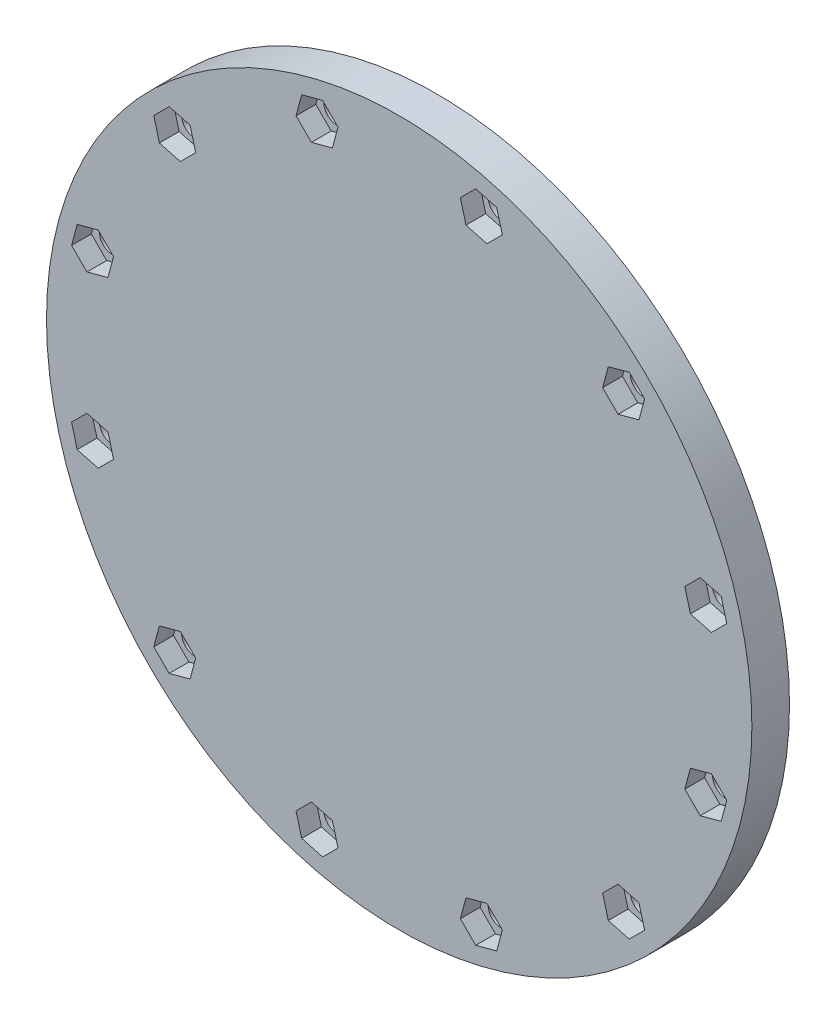
SolidWorks part; units mm, degrees
ref_plane "Front" through (0, 0, 0) normal (0, 0, 1) x (1, 0, 0)
ref_plane "Top" through (0, 0, 0) normal (0, 1, 0) x (1, 0, 0)
ref_plane "Right" through (0, 0, 0) normal (1, 0, 0) x (0, 0, -1)
sketch "Sketch1" plane through (0, 0, 0) normal (0, 0, 1) x (1, 0, 0)
  circle A0 centre (0, 0) radius 75
  dimension "D1" = 150
extrude "Boss-Extrude1" add sketch "Sketch1" along normal blind 8
hole_wizard "M5 Clearance Hole1" positions "Sketch3" profile "Sketch5" hole size "M5" standard "ANSI Metric" end condition up to next
sketch "Sketch3" plane through (0, 0, 0) normal (0, 0, -1) x (-1, 0, 0)
  line L14 (0, 0) -> (0, -75) construction
  line L15 (17.4703, -65.2) -> (-17.4703, 65.2) construction
  line L17 (65.2, 17.4703) -> (-65.2, -17.4703) construction
  line L19 (47.7297, 47.7297) -> (-47.7297, -47.7297) construction
  line L21 (0, 0) -> (17.4703, -65.2) construction
  line L23 (-17.4703, -65.2) -> (17.4703, 65.2) construction
  line L24 (-65.2, 17.4703) -> (65.2, -17.4703) construction
  line L26 (-47.7297, 47.7297) -> (47.7297, -47.7297) construction
  circle A1 centre (0, 0) radius 75 construction
  circle A3 centre (0, 0) radius 67.5 construction
  point P5 (-47.7297, 47.7297)
  point P11 (65.2, -17.4703)
  point P13 (47.7297, -47.7297)
  point P21 (-65.2, 17.4703)
  point P62 (-17.4703, 65.2)
  point P64 (-65.2, -17.4703)
  point P66 (-47.7297, -47.7297)
  point P68 (17.4703, -65.2)
  point P70 (17.4703, -65.2)
  point P72 (65.2, 17.4703)
  point P74 (47.7297, 47.7297)
  point P450 (17.4703, 65.2)
  point P453 (-17.4703, -65.2)
  dimension "D1" = 30
  dimension "D2" = 135
  dimension "D3" = 30
  dimension "D4" = 15
  dimension "D5" = 30
  dimension "D6" = 30
  dimension "D7" = 30
sketch "Sketch5" plane through (17.4703, -65.2, 0) normal (1, 0, 0) x (0, 1, 0)
  line L0 (0, 0) -> (0, 8)
  line L1 (0, 8) -> (2.75, 8)
  line L2 (2.75, 8) -> (2.75, 0)
  line L5 (2.75, 0) -> (0, 0)
  line L11 (0, -6.35) -> (0, 107.95) construction
  dimension "Thru Hole Dia." = 5.5
  dimension "Thru Hole Depth" = 8
sketch "Sketch6" plane through (0, 0, 8) normal (0, 0, -1) x (-1, 0, 0)
  line L0 (0, 0) -> (-47.7297, 47.7297) construction
  line L25 (-43.2683, 46.5343) -> (-44.4637, 50.9957)
  line L26 (-44.4637, 50.9957) -> (-48.9251, 52.1911)
  line L27 (-48.9251, 52.1911) -> (-52.1911, 48.9251)
  line L28 (-52.1911, 48.9251) -> (-50.9957, 44.4637)
  line L29 (-50.9957, 44.4637) -> (-46.5343, 43.2683)
  line L30 (-46.5343, 43.2683) -> (-43.2683, 46.5343)
  line L79 (-13.0089, 66.3954) -> (-16.2749, 69.6614)
  line L80 (-14.2043, 61.934) -> (-13.0089, 66.3954)
  line L81 (-18.6657, 60.7386) -> (-14.2043, 61.934)
  line L82 (-21.9317, 64.0046) -> (-18.6657, 60.7386)
  line L83 (-20.7363, 68.466) -> (-21.9317, 64.0046)
  line L84 (-16.2749, 69.6614) -> (-20.7363, 68.466)
  line L85 (21.9317, 64.0046) -> (20.7363, 68.466)
  line L86 (18.6657, 60.7386) -> (21.9317, 64.0046)
  line L87 (14.2043, 61.934) -> (18.6657, 60.7386)
  line L88 (13.0089, 66.3954) -> (14.2043, 61.934)
  line L89 (16.2749, 69.6614) -> (13.0089, 66.3954)
  line L90 (20.7363, 68.466) -> (16.2749, 69.6614)
  line L91 (50.9957, 44.4637) -> (52.1911, 48.9251)
  line L92 (46.5343, 43.2683) -> (50.9957, 44.4637)
  line L93 (43.2683, 46.5343) -> (46.5343, 43.2683)
  line L94 (44.4637, 50.9957) -> (43.2683, 46.5343)
  line L95 (48.9251, 52.1911) -> (44.4637, 50.9957)
  line L96 (52.1911, 48.9251) -> (48.9251, 52.1911)
  line L97 (66.3954, 13.0089) -> (69.6614, 16.2749)
  line L98 (61.934, 14.2043) -> (66.3954, 13.0089)
  line L99 (60.7386, 18.6657) -> (61.934, 14.2043)
  line L100 (64.0046, 21.9317) -> (60.7386, 18.6657)
  line L101 (68.466, 20.7363) -> (64.0046, 21.9317)
  line L102 (69.6614, 16.2749) -> (68.466, 20.7363)
  line L103 (64.0046, -21.9317) -> (68.466, -20.7363)
  line L104 (60.7386, -18.6657) -> (64.0046, -21.9317)
  line L105 (61.934, -14.2043) -> (60.7386, -18.6657)
  line L106 (66.3954, -13.0089) -> (61.934, -14.2043)
  line L107 (69.6614, -16.2749) -> (66.3954, -13.0089)
  line L108 (68.466, -20.7363) -> (69.6614, -16.2749)
  line L109 (44.4637, -50.9957) -> (48.9251, -52.1911)
  line L110 (43.2683, -46.5343) -> (44.4637, -50.9957)
  line L111 (46.5343, -43.2683) -> (43.2683, -46.5343)
  line L112 (50.9957, -44.4637) -> (46.5343, -43.2683)
  line L113 (52.1911, -48.9251) -> (50.9957, -44.4637)
  line L114 (48.9251, -52.1911) -> (52.1911, -48.9251)
  line L115 (13.0089, -66.3954) -> (16.2749, -69.6614)
  line L116 (14.2043, -61.934) -> (13.0089, -66.3954)
  line L117 (18.6657, -60.7386) -> (14.2043, -61.934)
  line L118 (21.9317, -64.0046) -> (18.6657, -60.7386)
  line L119 (20.7363, -68.466) -> (21.9317, -64.0046)
  line L120 (16.2749, -69.6614) -> (20.7363, -68.466)
  line L121 (-21.9317, -64.0046) -> (-20.7363, -68.466)
  line L122 (-18.6657, -60.7386) -> (-21.9317, -64.0046)
  line L123 (-14.2043, -61.934) -> (-18.6657, -60.7386)
  line L124 (-13.0089, -66.3954) -> (-14.2043, -61.934)
  line L125 (-16.2749, -69.6614) -> (-13.0089, -66.3954)
  line L126 (-20.7363, -68.466) -> (-16.2749, -69.6614)
  line L127 (-50.9957, -44.4637) -> (-52.1911, -48.9251)
  line L128 (-46.5343, -43.2683) -> (-50.9957, -44.4637)
  line L129 (-43.2683, -46.5343) -> (-46.5343, -43.2683)
  line L130 (-44.4637, -50.9957) -> (-43.2683, -46.5343)
  line L131 (-48.9251, -52.1911) -> (-44.4637, -50.9957)
  line L132 (-52.1911, -48.9251) -> (-48.9251, -52.1911)
  line L133 (-66.3954, -13.0089) -> (-69.6614, -16.2749)
  line L134 (-61.934, -14.2043) -> (-66.3954, -13.0089)
  line L135 (-60.7386, -18.6657) -> (-61.934, -14.2043)
  line L136 (-64.0046, -21.9317) -> (-60.7386, -18.6657)
  line L137 (-68.466, -20.7363) -> (-64.0046, -21.9317)
  line L138 (-69.6614, -16.2749) -> (-68.466, -20.7363)
  line L139 (-64.0046, 21.9317) -> (-68.466, 20.7363)
  line L140 (-60.7386, 18.6657) -> (-64.0046, 21.9317)
  line L141 (-61.934, 14.2043) -> (-60.7386, 18.6657)
  line L142 (-66.3954, 13.0089) -> (-61.934, 14.2043)
  line L143 (-69.6614, 16.2749) -> (-66.3954, 13.0089)
  line L144 (-68.466, 20.7363) -> (-69.6614, 16.2749)
  circle A6 centre (-47.7297, 47.7297) radius 4 construction
  circle A13 centre (-47.7297, 47.7297) radius 2.75 construction
  point P80 (0, 0)
  point P111 (-44.9013, 44.9013)
  dimension "D1" = 12
  dimension "D8" = 8
extrude "Cut-Extrude2" cut sketch "Sketch6" along normal blind 4.2
hole_wizard "Ø5.0mm Dowel Hole1" positions "Sketch8" profile "Sketch10" hole size "Ø5.0" standard "ANSI Metric"
sketch "Sketch8" plane through (0, 0, 0) normal (0, 0, -1) x (-1, 0, 0)
  circle A1 centre (0, 0) radius 67.5 construction
  point P545 (-30.1011, -60.4167)
  point P547 (-30.1011, 60.4167)
sketch "Sketch10" plane through (30.1011, 60.4167, 0) normal (1, 0, 0) x (0, 1, 0)
  line L0 (0, 0) -> (0, 6.4421)
  line L1 (0, 6.4421) -> (2.4, 5)
  line L2 (2.4, 5) -> (2.4, 0)
  line L5 (2.4, 0) -> (0, 0)
  line L10 (0, 6.4421) -> (-2.4, 5) construction
  line L11 (0, -6.35) -> (0, 107.95) construction
  dimension "Hole Dia." = 4.8
  dimension "Hole Depth" = 5
  dimension "Drill Angle" = 118
sketch "Sketch11" plane through (0, 0, 0) normal (0, 0, -1) x (-1, 0, 0)
  circle A0 centre (0, 0) radius 45.85
  dimension "D1" = 91.7
extrude "Cut-Extrude3" cut sketch "Sketch11" against normal blind 6
sketch "Sketch12" plane through (0, 0, 0) normal (0, 0, -1) x (-1, 0, 0)
  circle A0 centre (0, 0) radius 53.6575
  circle A1 centre (0, 0) radius 60.7695
  dimension "D1" = 107.315
  dimension "D2" = 7.112
extrude "Cut-Extrude4" cut sketch "Sketch12" against normal blind 4.1656
